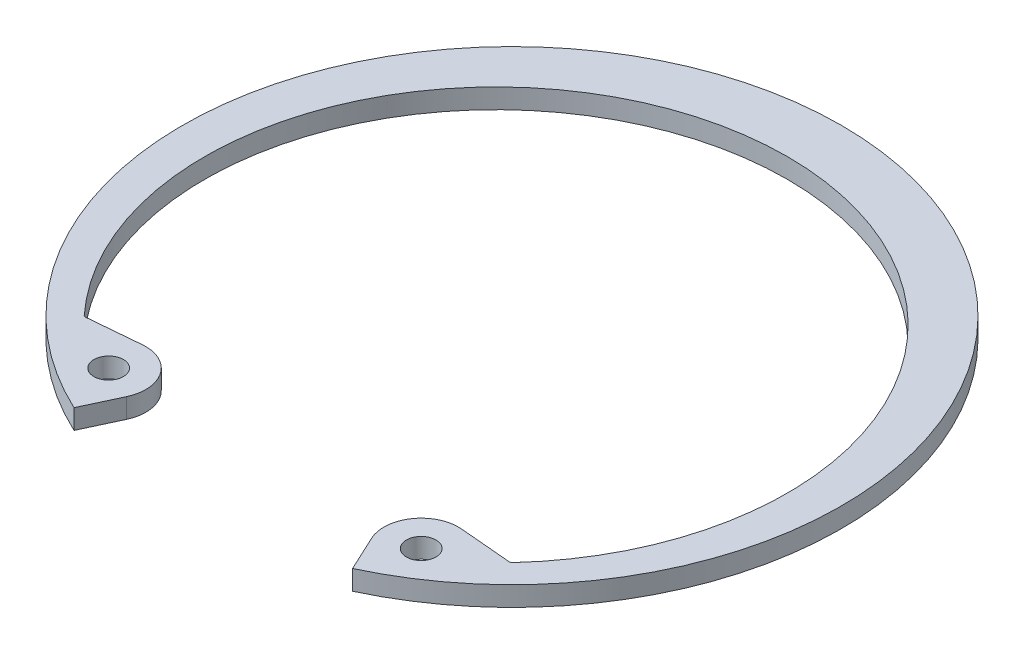
SolidWorks part; units mm, degrees
material "Cast Carbon Steel"
ref_plane "Front" through (0, 0, 0) normal (0, 0, 1) x (1, 0, 0)
ref_plane "Top" through (0, 0, 0) normal (0, 1, 0) x (1, 0, 0)
ref_plane "Right" through (0, 0, 0) normal (1, 0, 0) x (0, 0, -1)
sketch "Sketch2" plane through (0, 0, 0) normal (0, 1, 0) x (1, 0, 0)
  line L0 (0, 0) -> (0, -26.3144) construction
  line L1 (-17.0191, -17.1416) -> (-18.5402, -18.6737) construction
  line L2 (11.1209, -23.8489) -> (9.7847, -20.9834)
  line L3 (-11.1209, -23.8489) -> (-9.7847, -20.9834)
  line L4 (0, 21.9964) -> (0, 26.3144) construction
  line L5 (17.0191, -17.1416) -> (12.7371, -16.767)
  line L6 (-17.0191, -17.1416) -> (-12.7371, -16.767)
  line L7 (10.8895, -17.2159) -> (-0.6777, -24.5324) construction
  line L8 (-0.6777, -24.5324) -> (2.4996, -29.5555) construction
  line L9 (2.4996, -29.5555) -> (14.0667, -22.239) construction
  line L10 (10.8895, -17.2159) -> (14.0667, -22.239) construction
  line L11 (12.4781, -19.7275) -> (9.7847, -20.9834) construction
  line L12 (12.4781, -19.7275) -> (14.0667, -22.239) construction
  line L13 (10.8895, -17.2159) -> (-10.8895, -17.2159) construction
  line L14 (-10.8895, -17.2159) -> (-14.0667, -22.239) construction
  line L15 (-26.3144, 0) -> (26.3144, 0) construction
  arc A1 (11.1209, -23.8489) -> (-11.1209, -23.8489) centre (0, 0) ccw
  arc A2 (17.0191, -17.1416) -> (-17.0191, -17.1416) centre (0, -1.273) ccw
  circle A3 centre (0, 0) radius 26.3144 construction
  arc A4 (9.7847, -20.9834) -> (12.7371, -16.767) centre (12.4781, -19.7275) cw
  arc A5 (-9.7847, -20.9834) -> (-12.7371, -16.767) centre (-12.4781, -19.7275) ccw
  circle A6 centre (12.4781, -19.7275) radius 1.1811
  circle A7 centre (-12.4781, -19.7275) radius 1.1811
  arc A8 (17.0191, -17.1416) -> (-17.0191, -17.1416) centre (0, -1.273) cw construction
  circle A9 centre (0, 0) radius 18.0975 construction
  point P5 (12.4781, -19.7275)
  point P10 (10.8895, -17.2159)
  dimension "D1" = 60
  dimension "D2" = 60
  dimension "L" = 36.195
  dimension "R" = 2.3622
  dimension "Df" = 52.6288
  dimension "H" = 5.9436
  dimension "Angle" = 25
  dimension "Sec. Max" = 4.318
  dimension "Sec. Min" = 2.159
extrude "Extrude1" add sketch "Sketch2" against normal blind 1.5748
fillet "Fillet1" radius 0.254 2 edges at (-17.0191, -0.7874, 17.1416) (17.0191, -0.7874, 17.1416)
sketch "Sketch3" plane through (0, 0, 0) normal (1, 0, 0) x (0, 0, -1)
  line L0 (-23.8125, -16.4592) -> (-23.8125, -1.651)
  line L1 (-23.8125, -1.651) -> (-25.2603, -1.651)
  line L2 (-25.2603, -1.651) -> (-25.2603, 0.0762)
  line L3 (-25.2603, 0.0762) -> (-23.8125, 0.0762)
  line L4 (-23.8125, 0.0762) -> (-23.8125, 2.4384)
  line L5 (-23.8125, -16.4592) -> (-26.7081, -16.4592)
  line L6 (-23.8125, -1.651) -> (0, -1.651) construction
  line L7 (-23.8125, 2.4384) -> (-26.7081, 2.4384)
  line L8 (0, 130.3401) -> (0, 164.6301) construction
  line L9 (0, -1.651) -> (0, 0.0762) construction
  line L10 (0, 0.0762) -> (-23.8125, 0.0762) construction
  line L11 (-25.2603, -0.7874) -> (0, -0.7874) construction
  line L12 (0, -135.0899) -> (0, 130.3401) construction
  line L13 (-17.05, -1.5748) -> (21.9964, -1.5748) construction
  line L14 (-26.7081, -16.4592) -> (-26.7081, 2.4384)
  dimension "Shaft Lg" = 18.8976
  dimension "D1" = 0.7874
  dimension "D2" = 1.4478
  dimension "D4" = 1.4478
  dimension "D3" = 2.3622
revolve "Revolve1" [suppressed] add sketch "Sketch3" angle 360 about L8
delete or keep bodies "Body-Delete1" [suppressed] type delete bodies bodies 116
equation "\"D3@Sketch3\" = \"Shaft Lg@Sketch3\"/8"
equation "\"Shaft Lg@Sketch3\" = \"D1@Extrude1\"*12"
equation "\"D1@Sketch3\" = \"D1@Extrude1\"/2"
equation "\"D2@Sketch3\" = \"D4@Sketch3\""
